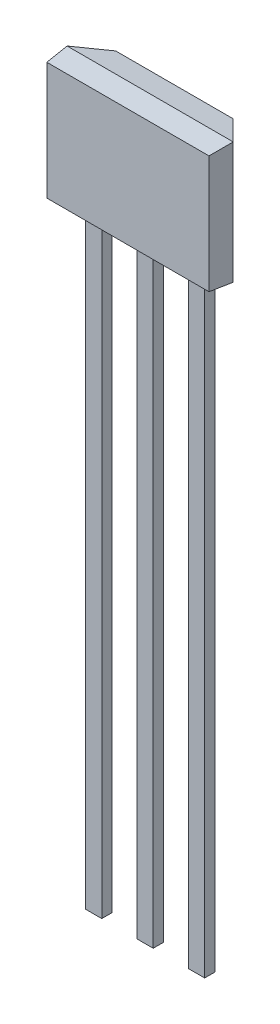
SolidWorks part; units mm, degrees
ref_plane "前基準面" through (0, 0, 0) normal (0, 0, 1) x (1, 0, 0)
ref_plane "上基準面" through (0, 0, 0) normal (0, 1, 0) x (1, 0, 0)
ref_plane "右基準面" through (0, 0, 0) normal (1, 0, 0) x (0, 0, -1)
sketch "草圖1" plane through (0, 0, 0) normal (0, 0, 1) x (1, 0, 0)
  line L1 (-2.05, 1.5) -> (2.05, 1.5)
  line L2 (-2.05, 1.5) -> (-2.05, -1.5)
  line L3 (-2.05, -1.5) -> (2.05, -1.5)
  line L4 (2.05, 1.5) -> (2.05, -1.5)
  line L5 (-2.05, 1.5) -> (2.05, -1.5) construction
  line L6 (-2.05, -1.5) -> (2.05, 1.5) construction
  point P0 (0, 0)
  dimension "D1" = 4.1
  dimension "D2" = 3
extrude "填料-伸長1" add sketch "草圖1" along normal blind 1.15
sketch "草圖2" plane through (0, -1.5, 0) normal (0, -1, 0) x (1, 0, 0)
  line L0 (-2.05, 1.15) -> (-2.05, 0.6)
  line L1 (-2.05, 1.15) -> (-2.05, 0) construction
  line L2 (-2.05, 0.6) -> (-2.0019, 1.15)
  line L3 (-2.05, 1.15) -> (2.05, 1.15) construction
  line L4 (-2.0019, 1.15) -> (-2.05, 1.15)
  line L5 (0, 0) -> (0, 1.15) construction
  line L6 (-2.05, 0.6) -> (-1.45, 0)
  line L7 (-2.05, 0) -> (2.05, 0) construction
  line L8 (-1.45, 0) -> (-2.05, 0)
  line L9 (-2.05, 0) -> (-2.05, 0.6)
  line L10 (2.05, 0) -> (2.05, 0.6)
  line L11 (1.45, 0) -> (2.05, 0)
  line L12 (2.05, 0.6) -> (1.45, 0)
  line L13 (2.0019, 1.15) -> (2.05, 1.15)
  line L14 (2.05, 0.6) -> (2.0019, 1.15)
  line L15 (2.05, 1.15) -> (2.05, 0.6)
  line M7 (-2.05, 0) -> (2.05, 0)
  line M8 (2.05, 0) -> (2.05, 1.15)
  line M10 (-2.05, 1.15) -> (-2.05, 0)
  dimension "D1" = 0.55
  dimension "D2" = 5
  dimension "D3" = 45
extrude "除料-伸長1" cut sketch "草圖2" against normal through all contours L6 M10 M7 | L12 M8 M7 | L2 L4 L0 | L14 L13 L15
ref_plane "平面1" through (2.5, 0, 0) normal (1, 0, 0) x (0, 0, -1)
sketch "草圖3" plane through (2.5, 0, 0) normal (1, 0, 0) x (0, 0, -1)
  line L0 (-1.15, -1.5) -> (-0.6, -1.5)
  line L1 (-0.6, -1.5) -> (-1.15, -1.4519)
  line L2 (-1.15, 1.5) -> (-1.15, -1.5) construction
  line L3 (-1.15, -1.4519) -> (-1.15, -1.5)
  line L4 (-0.6, -1.5) -> (0, -1.3942)
  line L5 (0, 1.5) -> (0, -1.5) construction
  line L6 (0, -1.3942) -> (0, -1.5)
  line L7 (0, -1.5) -> (-0.6, -1.5)
  line L8 (0, 0) -> (-1.15, 0) construction
  line L9 (0, 1.5) -> (-0.6, 1.5)
  line L10 (0, 1.3942) -> (0, 1.5)
  line L11 (-0.6, 1.5) -> (0, 1.3942)
  line L12 (-1.15, 1.4519) -> (-1.15, 1.5)
  line L13 (-0.6, 1.5) -> (-1.15, 1.4519)
  line L14 (-1.15, 1.5) -> (-0.6, 1.5)
  dimension "D1" = 5
  dimension "D2" = 10
extrude "除料-伸長2" cut sketch "草圖3" against normal through all contours L7 L6 L4 | L1 L3 L0 | L13 L12 L14 | L11 L10 L9
ref_plane "平面2" through (0, 0, 0.6) normal (0, 0, 1) x (1, 0, 0)
sketch "草圖5" plane through (0, 0, 0.6) normal (0, 0, 1) x (1, 0, 0)
  line L0 (-1.27, -1.5) -> (-1.27, -16.5) construction
  line L1 (-2.05, -1.5) -> (2.05, -1.5) construction
  line L2 (0, -1.5) -> (0, -16.5) construction
  line L3 (1.27, -1.5) -> (1.27, -16.5) construction
  line L5 (-1.47, -1.4) -> (-1.07, -1.4)
  line L6 (-1.47, -1.4) -> (-1.47, -16.6)
  line L7 (-1.47, -16.6) -> (-1.07, -16.6)
  line L8 (-1.07, -1.4) -> (-1.07, -16.6)
  line L9 (-1.47, -1.4) -> (-1.07, -16.6) construction
  line L10 (-1.47, -16.6) -> (-1.07, -1.4) construction
  line L11 (-0.2, -1.4) -> (0.2, -1.4)
  line L12 (-0.2, -1.4) -> (-0.2, -16.6)
  line L13 (-0.2, -16.6) -> (0.2, -16.6)
  line L14 (0.2, -1.4) -> (0.2, -16.6)
  line L15 (-0.2, -1.4) -> (0.2, -16.6) construction
  line L16 (-0.2, -16.6) -> (0.2, -1.4) construction
  line L17 (1.07, -1.4) -> (1.47, -1.4)
  line L18 (1.07, -1.4) -> (1.07, -16.6)
  line L19 (1.07, -16.6) -> (1.47, -16.6)
  line L20 (1.47, -1.4) -> (1.47, -16.6)
  line L21 (1.07, -1.4) -> (1.47, -16.6) construction
  line L22 (1.07, -16.6) -> (1.47, -1.4) construction
  point P9 (0, -9)
  point P10 (-1.27, -9)
  point P19 (1.27, -9)
  dimension "D1" = 1.27
  dimension "D2" = 1.27
  dimension "D3" = 15
  dimension "D4" = 0.4
  dimension "D5" = 0.4
  dimension "D6" = 0.4
  dimension "D7" = 0.1
  dimension "D8" = 0.1
  dimension "D9" = 0.1
extrude "填料-伸長2" add sketch "草圖5" along normal blind 0.125 and the other way blind 0.125 separate body
ref_plane "平面3" through (0, 0, 0.41) normal (0, 0, 1) x (1, 0, 0)
sketch "草圖7" plane through (0, 0, 0.41) normal (0, 0, 1) x (1, 0, 0)
  line L0 (0, 0.79) -> (0, 0) construction
  circle A0 centre (0, 0.79) radius 0.15
  dimension "D2" = 0.3
  dimension "D1" = 0.79
extrude "填料-伸長3" add sketch "草圖7" along normal blind 0.1 separate body
